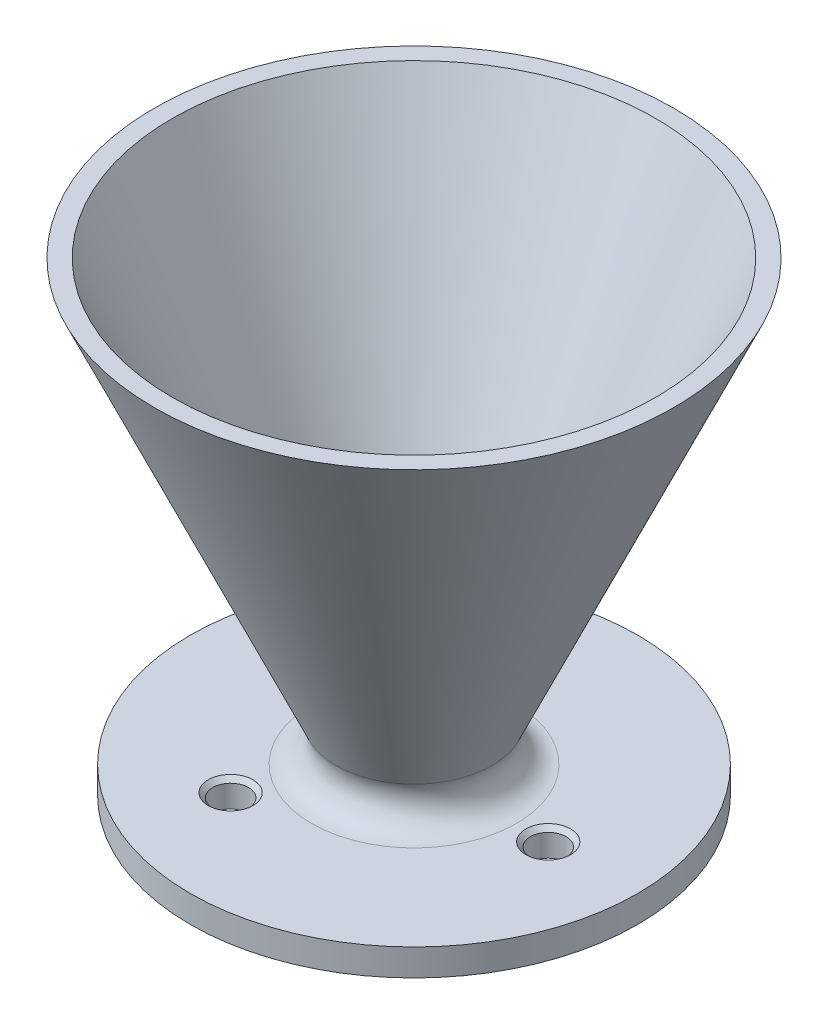
SolidWorks part; units mm, degrees
ref_plane "Front Plane" through (0, 0, 0) normal (0, 0, 1) x (1, 0, 0)
ref_plane "Top Plane" through (0, 0, 0) normal (0, 1, 0) x (1, 0, 0)
ref_plane "Right Plane" through (0, 0, 0) normal (1, 0, 0) x (0, 0, -1)
sketch "Sketch1" plane through (0, 0, 0) normal (0, 1, 0) x (1, 0, 0)
  circle A0 centre (0, 0) radius 4.8
  circle A1 centre (0, 0) radius 15 construction
  circle A2 centre (0, 0) radius 25
  dimension "D1" = 9.6
  dimension "D2" = 30
  dimension "D3" = 50
extrude "Boss-Extrude1" add sketch "Sketch1" along normal blind 3
sketch "Sketch5" plane through (0, 3, 0) normal (0, 1, 0) x (1, 0, 0)
  line L0 (0, 0) -> (15, 0) construction
  circle A0 centre (0, 0) radius 15
  circle A1 centre (15, 0) radius 2
  circle A2 centre (-7.5, -12.9904) radius 2
  circle A3 centre (-7.5, 12.9904) radius 2
  point P3 (15, 0)
  point P8 (-7.5, -12.9904)
  point P10 (-7.5, 12.9904)
  dimension "D1" = 30
  dimension "D2" = 4
  dimension "D4" = 15
  dimension "D3" = 3
hole_wizard "Ø4.0 (4) Diameter Hole1" positions "Sketch5" profile "Sketch7" hole size "Ø4.0" standard "ANSI Metric" end condition up to next
sketch "Sketch7" plane through (-7.5, 3, -12.9904) normal (1, 0, 0) x (0, 0, 1)
  line L0 (0, 0) -> (0, 3)
  line L1 (0, 3) -> (2, 3)
  line L2 (2, 3) -> (2, 0.5)
  line L3 (2, 0.5) -> (2.5, 0)
  line L5 (2.5, 0) -> (0, 0)
  line L6 (-2, 0.5) -> (-2.5, 0) construction
  line L11 (0, -6.35) -> (0, 107.95) construction
  dimension "Thru Hole Dia." = 4
  dimension "Thru Hole Depth" = 3
  dimension "Near C'Sink Dia." = 5
  dimension "Near C'Sink Angle" = 90
sketch "Sketch8" plane through (0, 0, 0) normal (0, 0, 1) x (1, 0, 0)
  line L0 (0, 0) -> (0, 50)
  line L1 (-4.8, 3) -> (4.8, 3) construction
  line L2 (27, 52) -> (29, 52)
  line L3 (0, 52) -> (27, 52) construction
  line L4 (4.8, 3) -> (0, 3)
  line L5 (0, 50) -> (0, 52)
  line L6 (4.8, 3) -> (27, 52)
  line L7 (4.8, 3) -> (6.8, 3)
  line L8 (29, 52) -> (6.8, 3)
  point P6 (0, 50)
  point P11 (0, 50)
  dimension "D1" = 50
  dimension "D2" = 2
  dimension "D3" = 2
  dimension "D4" = 27
  dimension "D5" = 2
revolve "Revolve1" add sketch "Sketch8" angle 360 about L0
fillet "Fillet2" radius 3 1 edges at (0, 3, -6.8)
